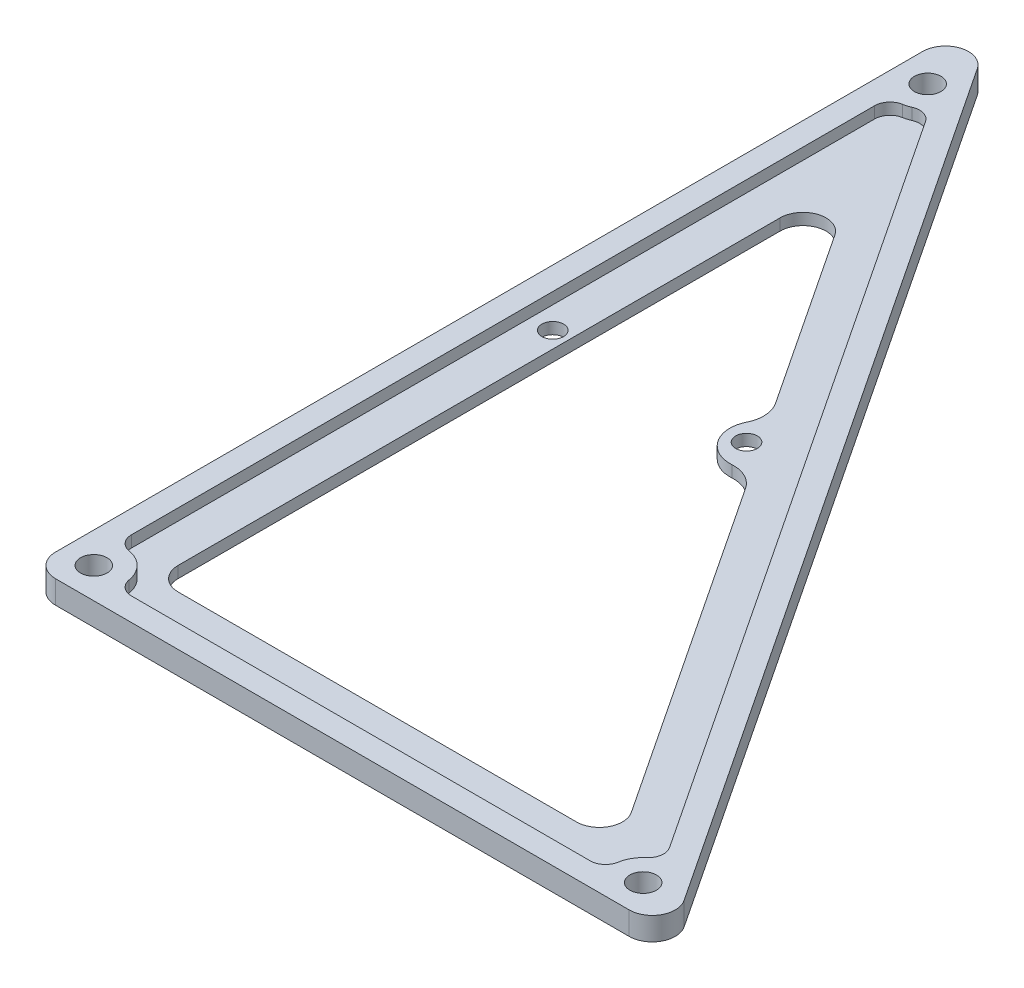
SolidWorks part; units mm, degrees
ref_plane "Front Plane" through (0, 0, 0) normal (0, 0, 1) x (1, 0, 0)
ref_plane "Top Plane" through (0, 0, 0) normal (0, 1, 0) x (1, 0, 0)
ref_plane "Right Plane" through (0, 0, 0) normal (1, 0, 0) x (0, 0, -1)
sketch "Sketch1" plane through (0, 0, 0) normal (0, 1, 0) x (1, 0, 0)
  line L0 (0, 0) -> (0, 172.72) construction
  line L1 (0, 172.72) -> (114.3, 0) construction
  line L2 (114.3, 0) -> (0, 0) construction
  line L3 (-6.35, 193.822) -> (126.1167, -6.35)
  line L4 (-6.35, -6.35) -> (-6.35, 193.822)
  line L5 (-6.35, 0) -> (-6.35, 172.72) construction
  line L6 (5.2955, 176.2244) -> (119.5955, 3.5044) construction
  line L7 (126.1167, -6.35) -> (-6.35, -6.35)
  line L8 (51.2979, 83.6967) -> (102.4833, 6.35)
  line L9 (6.35, 6.35) -> (6.35, 151.618)
  line L12 (6.35, 151.618) -> (39.1585, 102.0408)
  line L13 (6.35, 0) -> (6.35, 172.72) construction
  line L14 (102.4833, 6.35) -> (6.35, 6.35)
  arc A0 (39.5456, 95.7026) -> (45.6153, 86.5306) centre (45.2282, 92.8687) ccw
  arc A1 (39.1585, 102.0408) -> (39.5456, 95.7026) centre (33.863, 98.5364) cw
  arc A2 (51.2979, 83.6967) -> (45.6153, 86.5306) centre (46.0025, 80.1924) ccw
  point P20 (48.7326, 87.5733)
  dimension "D9" = 6.35
  dimension "D10" = 6.35
  dimension "D1" = 172.72
  dimension "D2" = 114.3
  dimension "D7" = 6.35
  dimension "D8" = 12.7
  dimension "D5" = 6.35
  dimension "D11" = 99.2188
  dimension "D3" = 6.35
  dimension "D4" = 6.35
  dimension "D6" = 6.35
extrude "Boss-Extrude1" add sketch "Sketch1" along normal blind 4.7625
fillet "Fillet5" radius 4.7625 6 edges at (6.35, 2.3813, -151.618) (-6.35, 2.3813, -193.822) (126.1167, 2.3813, 6.35) (-6.35, 2.3813, 6.35) (6.35, 2.3813, -6.35) (102.4833, 2.3813, -6.35)
sketch "Sketch2" plane through (0, 4.7625, 0) normal (0, 1, 0) x (1, 0, 0)
  point P0 (0, 0)
  point P1 (0, 172.72)
  point P8 (113.792, 0)
  dimension "D1" = 172.72
  dimension "D2" = 113.792
hole_wizard "#97 (0.0059) Diameter Hole1" positions "Sketch3" profile "Sketch4" hole size "#97" standard "ANSI Inch" end condition through all
sketch "Sketch3" plane through (0, 4.7625, 0) normal (0, 1, 0) x (1, 0, 0)
  point P0 (0, 172.72)
  point P3 (0, 0)
  point P6 (113.792, 0)
sketch "Sketch4" plane through (0, 4.7625, -172.72) normal (1, 0, 0) x (0, 0, 1)
  line L0 (0, 0) -> (0, 4.7625)
  line L1 (0, 4.7625) -> (2.75, 4.7625)
  line L2 (2.75, 4.7625) -> (2.75, 0)
  line L5 (2.75, 0) -> (0, 0)
  line L11 (0, -6.35) -> (0, 107.95) construction
  dimension "Thru Hole Dia." = 5.5
  dimension "Thru Hole Depth" = 4.7625
sketch "Sketch5" plane through (0, 4.7625, 0) normal (0, 1, 0) x (1, 0, 0)
  line L4 (-6.35, 177.9955) -> (-6.35, -1.5875) construction
  line L5 (-1.5875, -6.35) -> (117.2542, -6.35) construction
  line L7 (117.2542, -1.5875) -> (-1.5875, 177.9955)
  line L8 (-1.5875, 177.9955) -> (-1.5875, -1.5875)
  line L9 (-1.5875, -1.5875) -> (117.2542, -1.5875)
  line L10 (110.252, 8.9936) -> (6.5069, 165.764)
  line L11 (-1.5875, 163.3282) -> (-1.5875, 9.3918)
  line L12 (9.3918, -1.5875) -> (104.4002, -1.5875)
  arc A3 (1.0583, 166.4588) -> (2.5728, 166.9145) centre (0, 172.72) ccw
  arc A4 (6.2612, 1.0583) -> (1.0583, 6.2612) centre (0, 0) ccw
  arc A5 (109.6668, 4.8276) -> (107.5308, 1.0583) centre (113.792, 0) ccw
  arc A6 (-1.5875, 9.3918) -> (1.0583, 6.2612) centre (1.5875, 9.3918) ccw
  arc A7 (6.2612, 1.0583) -> (9.3918, -1.5875) centre (9.3918, 1.5875) ccw
  arc A8 (107.5308, 1.0583) -> (104.4002, -1.5875) centre (104.4002, 1.5875) cw
  arc A9 (110.252, 8.9936) -> (109.6668, 4.8276) centre (107.6043, 7.2414) cw
  arc A10 (2.5728, 166.9145) -> (6.5069, 165.764) centre (3.8591, 164.0118) cw
  arc A11 (1.0583, 166.4588) -> (-1.5875, 163.3282) centre (1.5875, 163.3282) ccw
  dimension "D2" = 3.175
  dimension "D3" = 3.175
  dimension "D4" = 3.175
  dimension "D5" = 3.175
  dimension "D6" = 3.175
  dimension "D7" = 3.175
  dimension "D1" = 4.7625
extrude "Cut-Extrude1" cut sketch "Sketch5" against normal blind 2.3813
sketch "Sketch6" plane through (0, 2.3813, 0) normal (0, 1, 0) x (1, 0, 0)
  line L0 (-1.5875, 163.3282) -> (-1.5875, 9.3918) construction
  line L2 (-1.5875, -6.35) -> (117.2542, -6.35) construction
  point P0 (2.9845, 92.075)
  point P1 (0, 0)
  point P4 (43.1165, 92.075)
  dimension "D1" = 4.572
  dimension "D2" = 40.132
  dimension "D3" = 98.425
hole_wizard "#8 Clearance Hole1" positions "Sketch7" profile "Sketch8" hole size "#8" standard "ANSI Inch" end condition through all
sketch "Sketch7" plane through (0, 2.3813, 0) normal (0, 1, 0) x (1, 0, 0)
  point P0 (2.9845, 92.075)
  point P3 (43.1165, 92.075)
sketch "Sketch8" plane through (2.9845, 2.3813, -92.075) normal (1, 0, 0) x (0, 0, 1)
  line L0 (0, 0) -> (0, 2.3812)
  line L1 (0, 2.3812) -> (2.2479, 2.3812)
  line L2 (2.2479, 2.3812) -> (2.2479, 0)
  line L5 (2.2479, 0) -> (0, 0)
  line L11 (0, -6.35) -> (0, 107.95) construction
  dimension "Thru Hole Dia." = 4.4958
  dimension "Thru Hole Depth" = 2.3813
